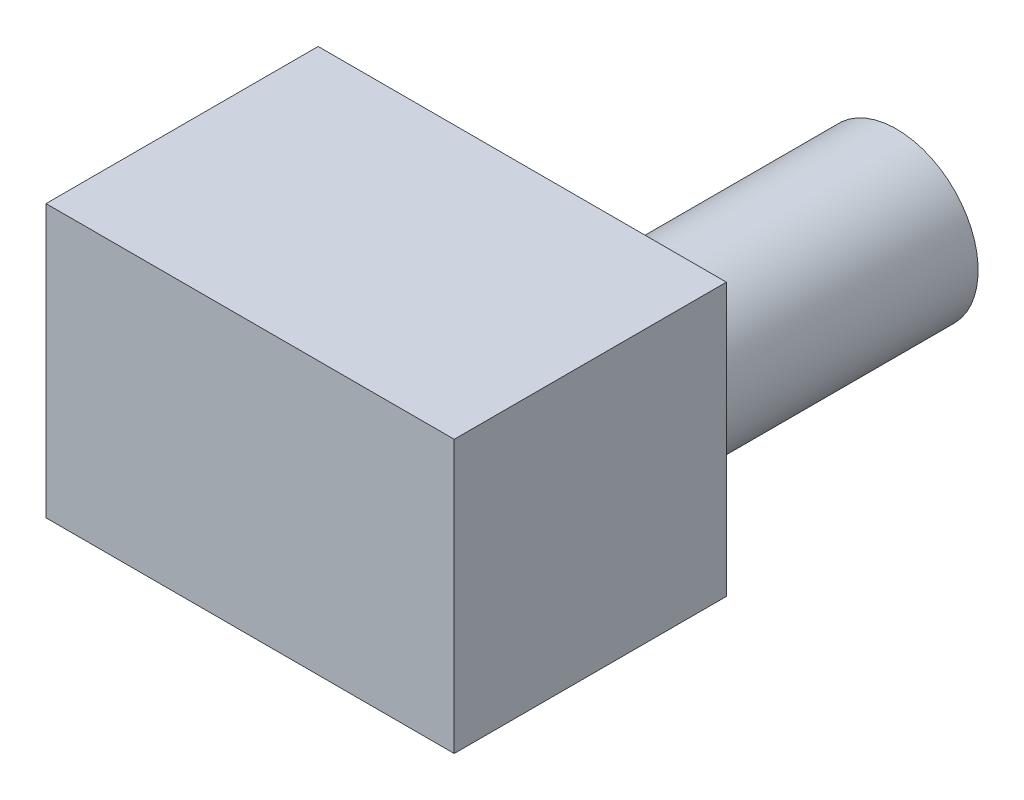
SolidWorks part; units mm, degrees
ref_plane "Ebene vorne" through (0, 0, 0) normal (0, 0, 1) x (1, 0, 0)
ref_plane "Ebene oben" through (0, 0, 0) normal (0, 1, 0) x (1, 0, 0)
ref_plane "Ebene rechts" through (0, 0, 0) normal (1, 0, 0) x (0, 0, -1)
sketch "Skizze1" plane through (0, 0, 0) normal (0, 0, 1) x (1, 0, 0)
  line L1 (-3.75, -2.5) -> (3.75, -2.5)
  line L2 (-3.75, -2.5) -> (-3.75, 2.5)
  line L3 (-3.75, 2.5) -> (3.75, 2.5)
  line L4 (3.75, -2.5) -> (3.75, 2.5)
  line L5 (-3.75, -2.5) -> (3.75, 2.5) construction
  line L6 (-3.75, 2.5) -> (3.75, -2.5) construction
  point P0 (0, 0)
  dimension "D1" = 5
  dimension "D2" = 7.5
extrude "Aufsatz-Linear austragen1" add sketch "Skizze1" along normal blind 5
sketch "Skizze2" plane through (0, 0, 0) normal (0, 0, -1) x (-1, 0, 0)
  line L1 (-3.75, 0) -> (0, 0)
  line L2 (-3.75, -2.5) -> (-3.75, 2.5) construction
  circle A0 centre (-1.875, 0) radius 1.5
  point P2 (0, 0)
  point P7 (-1.875, 0)
  dimension "D1" = 3
extrude "Aufsatz-Linear austragen2" add sketch "Skizze2" along normal blind 5 contours L1 A0 | L1 A0
